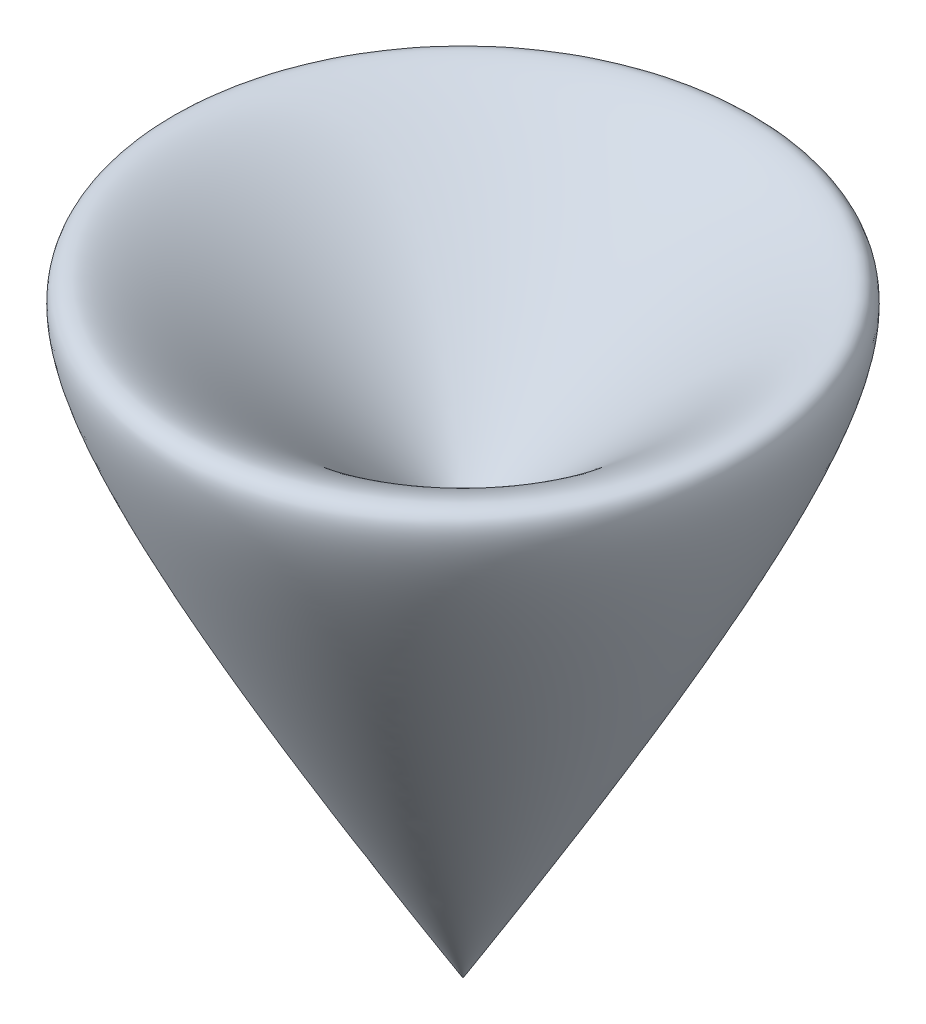
SolidWorks part; units mm, degrees
ref_plane "Front Plane" through (0, 0, 0) normal (0, 0, 1) x (1, 0, 0)
ref_plane "Top Plane" through (0, 0, 0) normal (0, 1, 0) x (1, 0, 0)
ref_plane "Right Plane" through (0, 0, 0) normal (1, 0, 0) x (0, 0, -1)
sketch "Sketch1" plane through (0, 0, 0) normal (0, 0, 1) x (1, 0, 0)
  line L0 (0, 50.2699) -> (0, -38.5792) construction
  line L1 (0, -38.5792) -> (0, 5.8453)
  spline S0 degree 2 poles (0, 5.8453) (69.1014, 76.3646) (0, -38.5792) knots 0 0 0 1 1 1
revolve "Revolve1" add sketch "Sketch1" angle 360 about L0
sketch "Sketch2" plane through (0, 0, 0) normal (0, 0, 1) x (1, 0, 0)
  text T0 "DANIEL"
